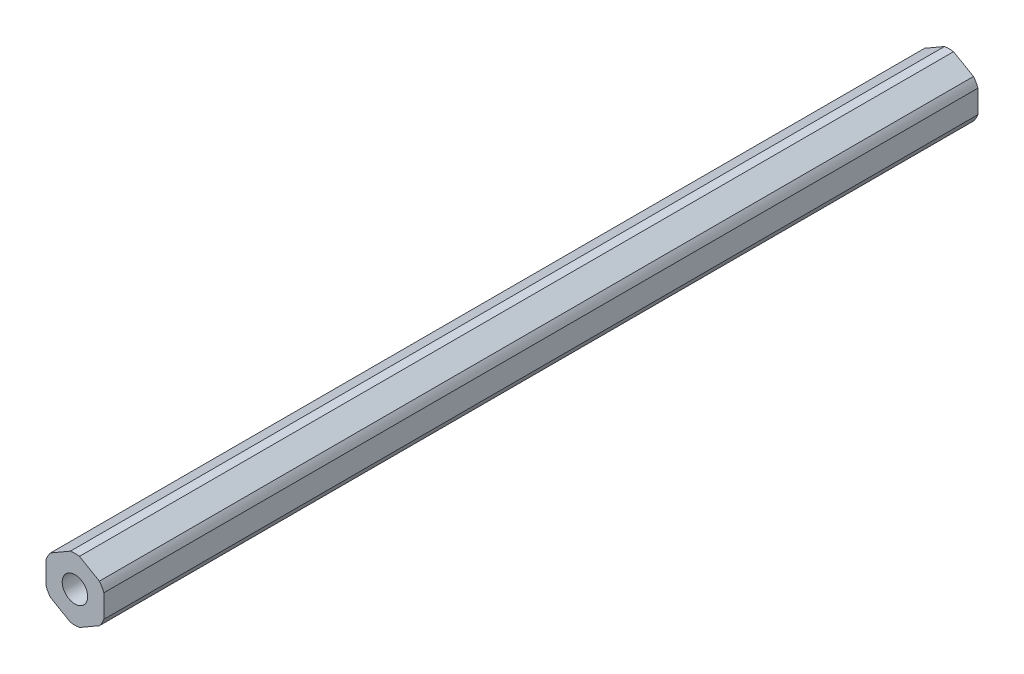
SolidWorks part; units mm, degrees
material "7075-T6 (SN)"
ref_plane "Front" through (0, 0, 0) normal (0, 0, 1) x (1, 0, 0)
ref_plane "Top" through (0, 0, 0) normal (0, 1, 0) x (1, 0, 0)
ref_plane "Right" through (0, 0, 0) normal (1, 0, 0) x (0, 0, -1)
sketch "Sketch1" plane through (0, 0, 0) normal (0, 0, 1) x (1, 0, 0)
  line L1 (0, 5.4993) -> (-4.7625, 2.7496)
  line L2 (-4.7625, 2.7496) -> (-4.7625, -2.7496)
  line L3 (-4.7625, -2.7496) -> (0, -5.4993)
  line L4 (0, -5.4993) -> (4.7625, -2.7496)
  line L5 (4.7625, -2.7496) -> (4.7625, 2.7496)
  line L6 (4.7625, 2.7496) -> (0, 5.4993)
  circle A0 centre (0, 0) radius 4.7625 construction
  dimension "D1" = 9.525
extrude "Shaft Boss" add sketch "Sketch1" along normal mid plane 914.4
sketch "Sketch2" plane through (0, 0, -457.2) normal (0, 0, -1) x (-1, 0, 0)
  circle A0 centre (0, 0) radius 5.1245
  circle A1 centre (0, 0) radius 7.6645
  dimension "D1" = 10.2489
  dimension "D2" = 2.54
extrude "Cut For Thunder Hex Round" cut sketch "Sketch2" against normal blind 914.4
sketch "Sketch3" plane through (0, 0, -457.2) normal (0, 0, -1) x (-1, 0, 0)
  circle A0 centre (0, 0) radius 2.0955
  dimension "D1" = 4.191
extrude "Center Hole Cut" cut sketch "Sketch3" against normal blind 914.4
ref_plane "Plane1" through (0, 0, 71.9105) normal (0, 0, -1) x (-1, 0, 0)
other "SurfaceCut1"
ref_plane "Plane2" through (0, 0, -71.9105) normal (0, 0, 1) x (1, 0, 0)
other "SurfaceCut2"
equation "\"HS\"=3 / 8"
equation "\"L\"= 36"
equation "\"D1@Sketch1\"=\"HS\""
equation "\"D1@Shaft Boss\" = \"L\""
equation "\"THOD\"=.4035"
equation "\"Fillet1\"      = \"suppressed\""
equation "\"Shaft Boss\"= \"unsuppressed\""
equation "\"D1@Sketch2\"=\"THOD\""
equation "\"D1@Cut For Thunder Hex Round\" = \"L\""
equation "\"Cut For Thunder Hex Round\"    = \"unsuppressed\""
equation "\"THID\"=.165"
equation "\"D1@Sketch3\"=\"THID\""
equation "\"D1@Center Hole Cut\" = \"L\""
equation "\"Center Hole Cut\"     = \"unsuppressed\""
